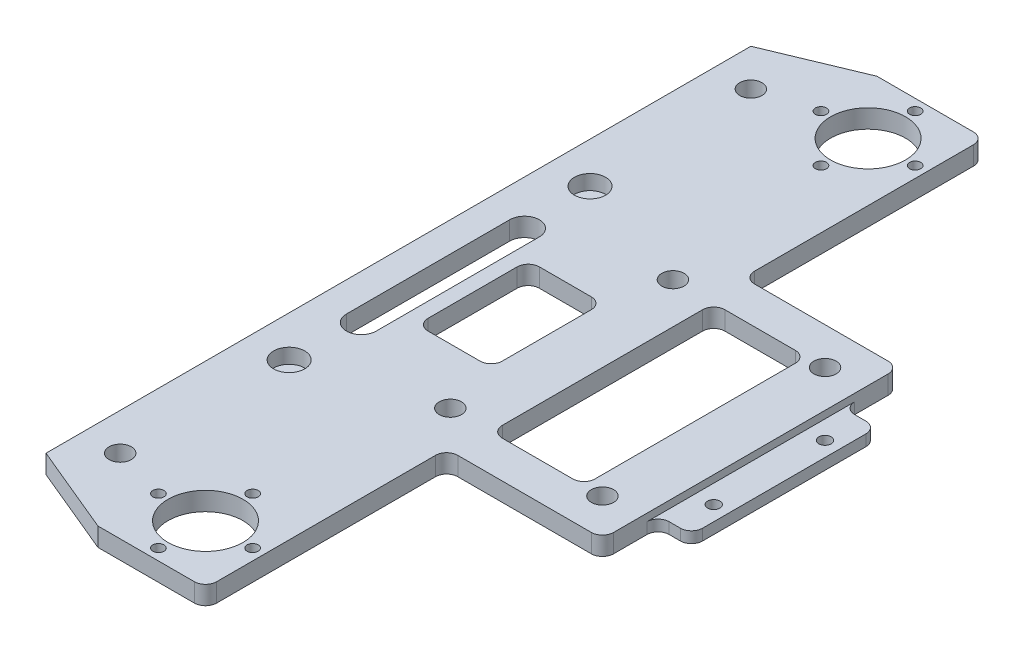
SolidWorks part; units mm, degrees
ref_plane "Plan de face" through (0, 0, 0) normal (0, 0, 1) x (1, 0, 0)
ref_plane "Plan de dessus" through (0, 0, 0) normal (0, 1, 0) x (1, 0, 0)
ref_plane "Plan de droite" through (0, 0, 0) normal (1, 0, 0) x (0, 0, -1)
sketch "Esquisse1" plane through (0, 0, 0) normal (0, 1, 0) x (1, 0, 0)
  line L0 (-104, 95) -> (-104, -95)
  line L1 (-104, 95) -> (-80, 105)
  line L2 (-80, 105) -> (-51, 105)
  line L3 (-104, -95) -> (-80, -105)
  line L4 (-80, -105) -> (-51, -105)
  line L5 (-51, 105) -> (-51, 40)
  line L6 (-51, 40) -> (-9, 40)
  line L7 (-9, 40) -> (-9, 25)
  line L8 (-9, 25) -> (0, 25)
  line L9 (0, 25) -> (0, -25)
  line L10 (0, -25) -> (-9, -25)
  line L11 (-9, -25) -> (-9, -40)
  line L12 (-9, -40) -> (-51, -40)
  line L13 (-51, -40) -> (-51, -105)
  line L14 (-92, 22) -> (-92, -22) construction
  line L15 (-49, 30) -> (-24, 30)
  line L16 (-49, 30) -> (-49, -30)
  line L17 (-49, -30) -> (-24, -30)
  line L18 (-24, 30) -> (-24, -30)
  line L19 (-88, 22) -> (-88, -22)
  line L20 (-96, 22) -> (-96, -22)
  line L22 (-84, 15) -> (-64, 15)
  line L23 (-84, 15) -> (-84, -15)
  line L24 (-84, -15) -> (-64, -15)
  line L25 (-64, 15) -> (-64, -15)
  circle A0 centre (-60, 30) radius 3
  circle A1 centre (-60, -30) radius 3
  circle A2 centre (-19, -30) radius 3
  circle A3 centre (-19, 30) radius 3
  arc A4 (-88, 22) -> (-96, 22) centre (-92, 22) ccw
  arc A5 (-96, -22) -> (-88, -22) centre (-92, -22) ccw
  circle A6 centre (-94, 85) radius 3
  circle A7 centre (-94, -85) radius 3
  circle A8 centre (-66.7, 89.3) radius 10.1
  circle A9 centre (-54, 89.3) radius 1.5
  circle A10 centre (-66.7, 102) radius 1.5
  circle A11 centre (-79.4, 89.3) radius 1.5
  circle A12 centre (-66.7, 76.6) radius 1.5
  circle A13 centre (-66.7, -89.3) radius 10.1
  circle A14 centre (-54, -89.3) radius 1.5
  circle A15 centre (-66.7, -76.6) radius 1.5
  circle A16 centre (-79.4, -89.3) radius 1.5
  circle A17 centre (-66.7, -102) radius 1.5
  point P29 (-92, 0)
  dimension "D18" = 6
  dimension "D21" = 4
  dimension "D27" = 6
  dimension "D36" = 20.2
  dimension "D37" = 3
  dimension "D44" = 20.2
  dimension "D45" = 3
  dimension "D1" = 190
  dimension "D2" = 24
  dimension "D3" = 10
  dimension "D4" = 29
  dimension "D5" = 29
  dimension "D6" = 10
  dimension "D7" = 24
  dimension "D8" = 50
  dimension "D9" = 9
  dimension "D10" = 80
  dimension "D11" = 42
  dimension "D12" = 65
  dimension "D13" = 26
  dimension "D14" = 25
  dimension "D15" = 60
  dimension "D16" = 55
  dimension "D17" = 10
  dimension "D19" = 11
  dimension "D20" = 5
  dimension "D22" = 44
  dimension "D23" = 43
  dimension "D24" = 85
  dimension "D25" = 85
  dimension "D26" = 10
  dimension "D28" = 20
  dimension "D29" = 30
  dimension "D30" = 15
  dimension "D31" = 4
  dimension "D32" = 12.7
  dimension "D33" = 12.7
  dimension "D34" = 12.7
  dimension "D35" = 12.7
  dimension "D38" = 3
  dimension "D39" = 3
  dimension "D40" = 12.7
  dimension "D41" = 12.7
  dimension "D42" = 12.7
  dimension "D43" = 12.7
  dimension "D46" = 3
extrude "Boss.-Extru.1" add sketch "Esquisse1" along normal blind 5
fillet "Congé1" radius 3 18 edges at (-51, 2.5, -40) (0, 2.5, 25) (0, 2.5, -25) (-9, 2.5, -25) (-51, 2.5, -105) (-9, 2.5, -40) (-9, 2.5, 25) (-9, 2.5, 40) (-51, 2.5, 40) (-51, 2.5, 105) (-64, 2.5, 15) (-84, 2.5, 15) (-84, 2.5, -15) (-64, 2.5, -15) (-49, 2.5, 30) (-24, 2.5, 30) (-24, 2.5, -30) (-49, 2.5, -30)
sketch "Esquisse3" plane through (0, 5, 0) normal (0, 1, 0) x (1, 0, 0)
  line L0 (-49, 27) -> (-49, -27) construction
  circle A0 centre (-93, 40.65) radius 4.2
  circle A1 centre (-93, -40.45) radius 4.2
  dimension "D1" = 81.1
  dimension "D2" = 8.4
  dimension "D3" = 40.65
  dimension "D4" = 44
extrude "Enlèv. mat.-Extru.2" cut sketch "Esquisse3" against normal blind 4
sketch "Esquisse4" plane through (0, 5, 0) normal (0, 1, 0) x (1, 0, 0)
  line L1 (-9, 28) -> (0, 28)
  line L2 (-9, 28) -> (-9, -28)
  line L3 (-9, -28) -> (0, -28)
  line L4 (0, 28) -> (0, -28)
extrude "Enlèv. mat.-Extru.3" cut sketch "Esquisse4" against normal blind 2
hole_wizard "Trou pour taraudage pour trou taraudé M41" positions "Esquisse6" profile "Esquisse5" hole size "M4" standard "Iso"
sketch "Esquisse6" plane through (0, 3, 0) normal (0, 1, 0) x (1, 0, 0)
  line L0 (0, -22) -> (0, 22) construction
  point P0 (-4, 15)
  point P2 (-4, -15)
  dimension "D1" = 30
  dimension "D2" = 15
  dimension "D3" = 4
sketch "Esquisse5" plane through (-4, 3, -15) normal (1, 0, 0) x (0, 0, 1)
  line L0 (0, 0) -> (0, 10.9914)
  line L1 (0, 10.9914) -> (1.65, 10)
  line L2 (1.65, 10) -> (1.65, 0)
  line L5 (1.65, 0) -> (0, 0)
  line L10 (0, 10.9914) -> (-1.65, 10) construction
  line L11 (0, -6.35) -> (0, 107.95) construction
  dimension "Diamètre du perçage" = 3.3
  dimension "Profondeur du perçage" = 10
  dimension "Angle de pointe" = 118
